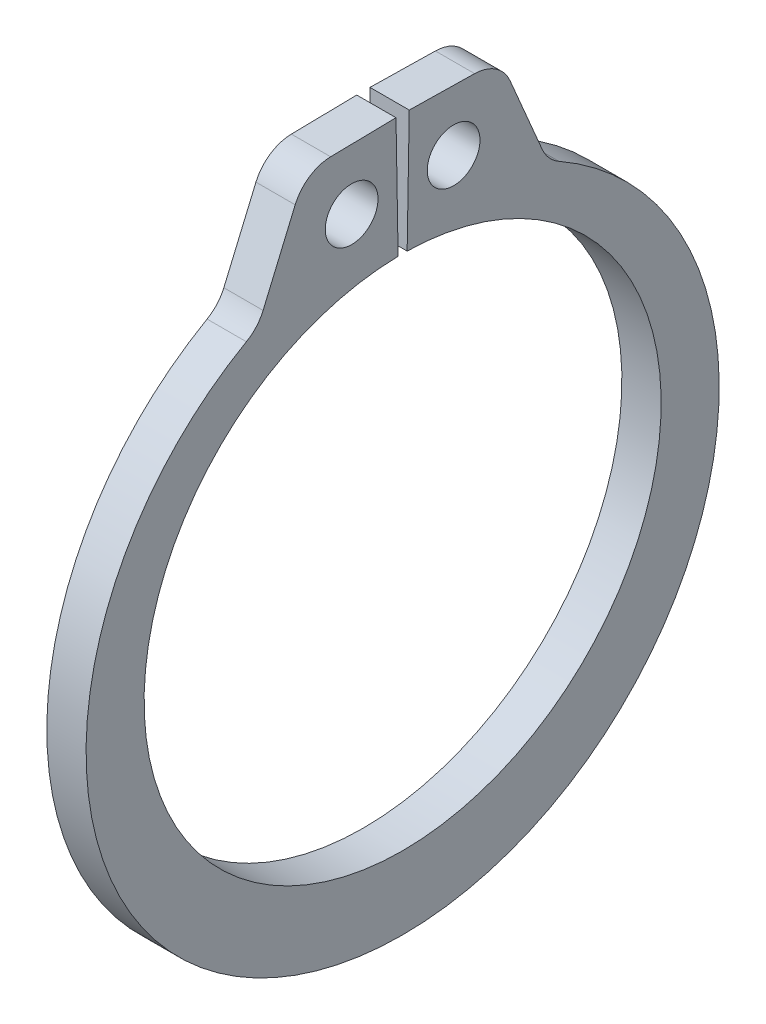
SolidWorks part; units mm, degrees
material "Cast Carbon Steel"
ref_plane "Front" through (0, 0, 0) normal (0, 0, 1) x (1, 0, 0)
ref_plane "Top" through (0, 0, 0) normal (0, 1, 0) x (1, 0, 0)
ref_plane "Right" through (0, 0, 0) normal (1, 0, 0) x (0, 0, -1)
sketch "Sketch1" plane through (0, 0, 0) normal (1, 0, 0) x (0, 0, -1)
  line L0 (0, 0) -> (0, 5.8547) construction
  line L1 (-0.1022, 5.8538) -> (-0.1501, 8.5966)
  line L2 (0.1501, 8.5966) -> (2.2071, 8.5607)
  line L3 (2.2071, 8.5607) -> (3.2813, 6.0365)
  line L4 (0.1022, 5.8538) -> (0.1501, 8.5966)
  line L5 (-0.1501, 8.5966) -> (-2.2071, 8.5607)
  line L6 (-2.2071, 8.5607) -> (-3.2813, 6.0365)
  line L7 (-3.2813, 6.0365) -> (-2.7961, 5.1439) construction
  line L8 (3.2813, 6.0365) -> (2.7961, 5.1439) construction
  line L9 (0, -5.8547) -> (0, -7.5057) construction
  line L10 (-2.2071, 8.5607) -> (-0.1022, 5.8538) construction
  line L11 (0, 5.8547) -> (0, 8.5979) construction
  line L12 (-5.8547, 0) -> (5.8547, 0) construction
  circle A0 centre (0, 0) radius 5.8547 construction
  arc A1 (-0.1022, 5.8538) -> (0.1022, 5.8538) centre (0, 0) ccw
  circle A3 centre (0, 0) radius 9.5885 construction
  circle A4 centre (-1.1547, 7.2072) radius 0.5969
  circle A5 centre (1.1547, 7.2072) radius 0.5969
  arc A6 (-3.2813, 6.0365) -> (3.2813, 6.0365) centre (0, -0.3371) ccw
  point P0 (0, -7.5057)
  dimension "A" = 11.7094
  dimension "Hole" = 1.1938
  dimension "Smin" = 1.016
  dimension "H" = 2.7432
  dimension "D2" = 2.0574
  dimension "Angle" = 1
extrude "Extrude1" add sketch "Sketch1" along normal mid plane 0.889
fillet "Fillet1" radius 0.889 4 edges at (0, 6.0365, 3.2813) (0, 6.0365, -3.2813) (0, 8.5607, 2.2071) (0, 8.5607, -2.2071)
equation "\"D2@Sketch1\"= \"H@Sketch1\" * .75"
equation "\"D1@Fillet1\" = \"D1@Extrude1\""
